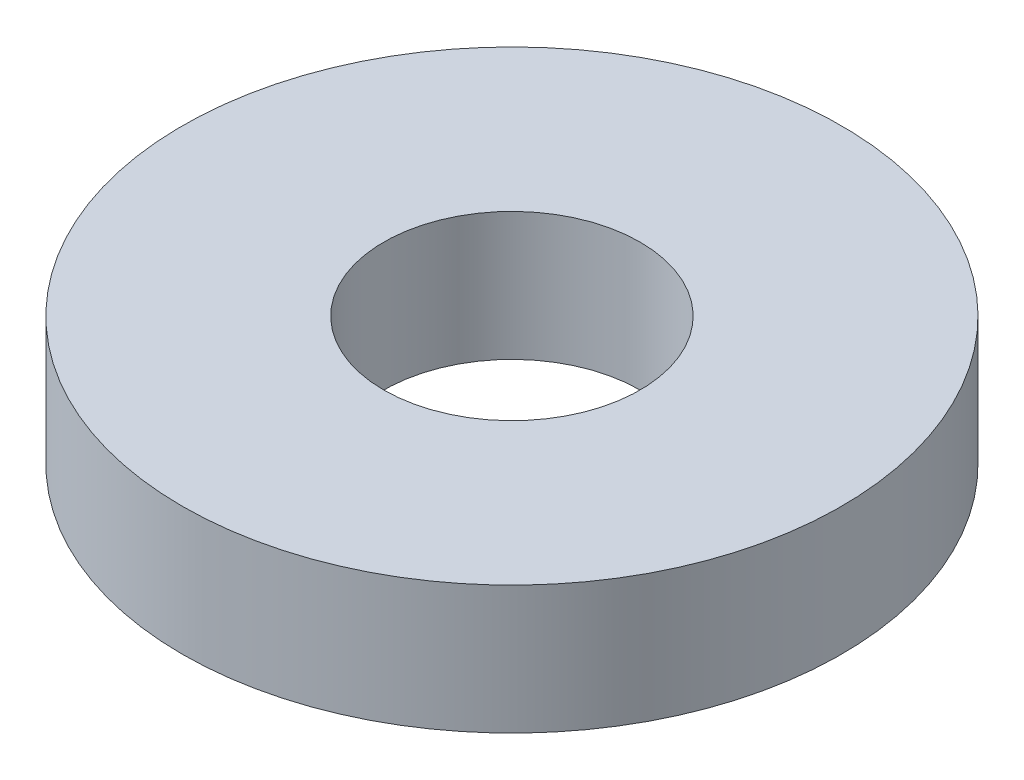
SolidWorks part; units mm, degrees
ref_plane "Спереди" through (0, 0, 0) normal (0, 0, 1) x (1, 0, 0)
ref_plane "Сверху" through (0, 0, 0) normal (0, 1, 0) x (1, 0, 0)
ref_plane "Справа" through (0, 0, 0) normal (1, 0, 0) x (0, 0, -1)
sketch "Эскиз1" plane through (0, 0, 0) normal (0, 1, 0) x (1, 0, 0)
  circle A0 centre (0, 0) radius 18
  circle A1 centre (0, 0) radius 7
extrude "Вытянуть1" add sketch "Эскиз1" along normal blind 7
